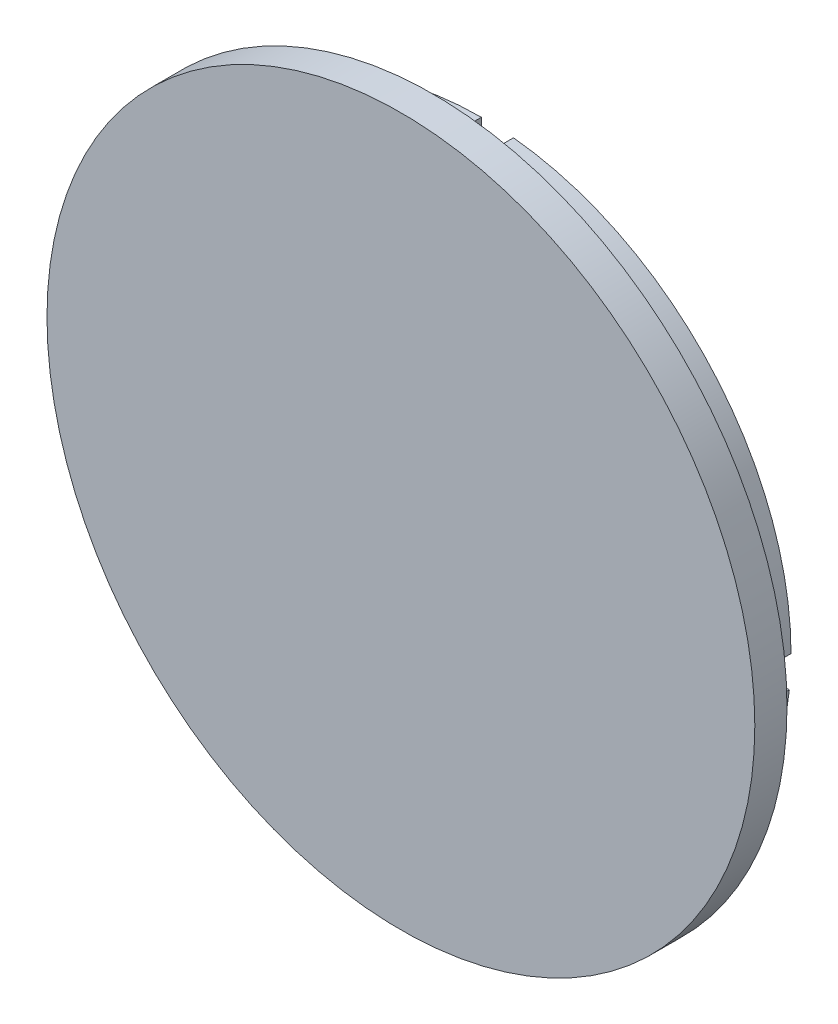
SolidWorks part; units mm, degrees
ref_plane "Piano frontale" through (0, 0, 0) normal (0, 0, 1) x (1, 0, 0)
ref_plane "Piano superiore" through (0, 0, 0) normal (0, 1, 0) x (1, 0, 0)
ref_plane "Piano destro" through (0, 0, 0) normal (1, 0, 0) x (0, 0, -1)
sketch "Schizzo1" plane through (0, 0, 0) normal (0, 0, 1) x (1, 0, 0)
  circle A0 centre (0, 0) radius 19.25
  circle A1 centre (0, 0) radius 18.25
  dimension "D1" = 38.5
  dimension "D2" = 1
extrude "Estrusione-Estrusione1" add sketch "Schizzo1" along normal blind 3
sketch "Schizzo2" plane through (0, 0, 3) normal (0, 0, 1) x (1, 0, 0)
  circle A0 centre (0, 0) radius 22
  dimension "D1" = 44
extrude "Estrusione-Estrusione2" add sketch "Schizzo2" along normal blind 2
sketch "Schizzo3" plane through (0, 0, 0) normal (0, 0, -1) x (-1, 0, 0)
  line L0 (0, 19.25) -> (0, 18.25)
  line L1 (-2, 19.25) -> (-2, 18.1401)
  line L2 (19.25, 0) -> (18.25, 0)
  line L3 (19.25, -2) -> (18.1401, -2)
  line L4 (-18.25, 0) -> (-19.25, 0)
  line L5 (0, -18.25) -> (0, -19.25)
  line L6 (19.25, 0) -> (-19.25, 0) construction
  line L7 (-18.1401, -2) -> (-19.25, -2)
  line L8 (0, 19.25) -> (0, -19.25) construction
  line L9 (-2, -18.1401) -> (-2, -19.25)
  line L10 (19.25, -2) -> (-19.25, -2) construction
  line L12 (-2, 19.25) -> (-2, -19.25) construction
  arc A0 (19.1458, -2) -> (19.25, 0) centre (0, 0) ccw
  circle A1 centre (0, 0) radius 19.25
  arc A2 (0, 19.25) -> (-2, 19.1458) centre (0, 0) ccw
  arc A3 (-2, -19.1458) -> (0, -19.25) centre (0, 0) ccw
  arc A4 (-19.25, 0) -> (-19.1458, -2) centre (0, 0) ccw
  circle A5 centre (0, 0) radius 18.25 construction
  arc A6 (-18.25, 0) -> (-18.1401, -2) centre (0, 0) ccw
  arc A7 (0, 18.25) -> (-2, 18.1401) centre (0, 0) ccw
  arc A8 (18.1401, -2) -> (18.25, 0) centre (0, 0) ccw
  arc A9 (-2, -18.1401) -> (0, -18.25) centre (0, 0) ccw
  circle M2 centre (0, 0) radius 19.25
  circle M3 centre (0, 0) radius 18.25
  dimension "D1" = 0
  dimension "D2" = 2
  dimension "D3" = 2
extrude "Taglio-Estrusione1" cut sketch "Schizzo3" against normal blind 3 contours L1 L0 M2 M3 | L7 L4 M3 M2 | L9 L5 M3 M2 | L3 L2 M2 M3
